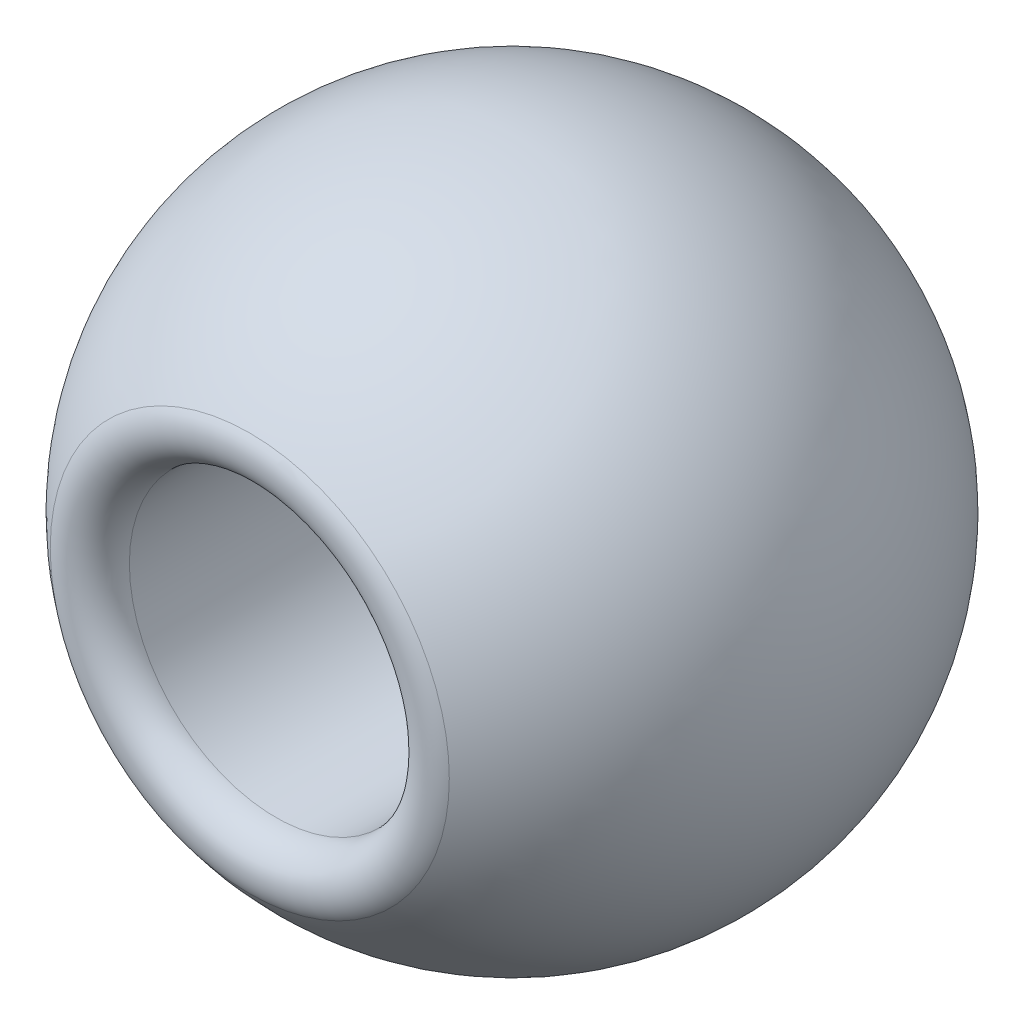
SolidWorks part; units mm, degrees
ref_plane "정면" through (0, 0, 0) normal (0, 0, 1) x (1, 0, 0)
ref_plane "윗면" through (0, 0, 0) normal (0, 1, 0) x (1, 0, 0)
ref_plane "우측면" through (0, 0, 0) normal (1, 0, 0) x (0, 0, -1)
sketch "스케치1" plane through (0, 0, 0) normal (0, 0, 1) x (1, 0, 0)
  line L0 (0, 11.7897) -> (0, -13.2661) construction
  line L1 (0, 10) -> (0, -10)
  arc A0 (0, 10) -> (0, -10) centre (0, 0) ccw
  dimension "D1" = 20
revolve "회전2" add sketch "스케치1" angle 360 about L0
sketch "스케치2" plane through (0, 0, 0) normal (0, 0, 1) x (1, 0, 0)
  circle A1 centre (0, 0) radius 4.45
  dimension "D1" = 8.9
extrude "컷-돌출1" cut sketch "스케치2" against normal mid plane 30 contours A1
fillet "필렛1" radius 1 2 edges at (-4.45, 0, 8.9553) (4.45, 0, -8.9553)
ref_point "점1"
